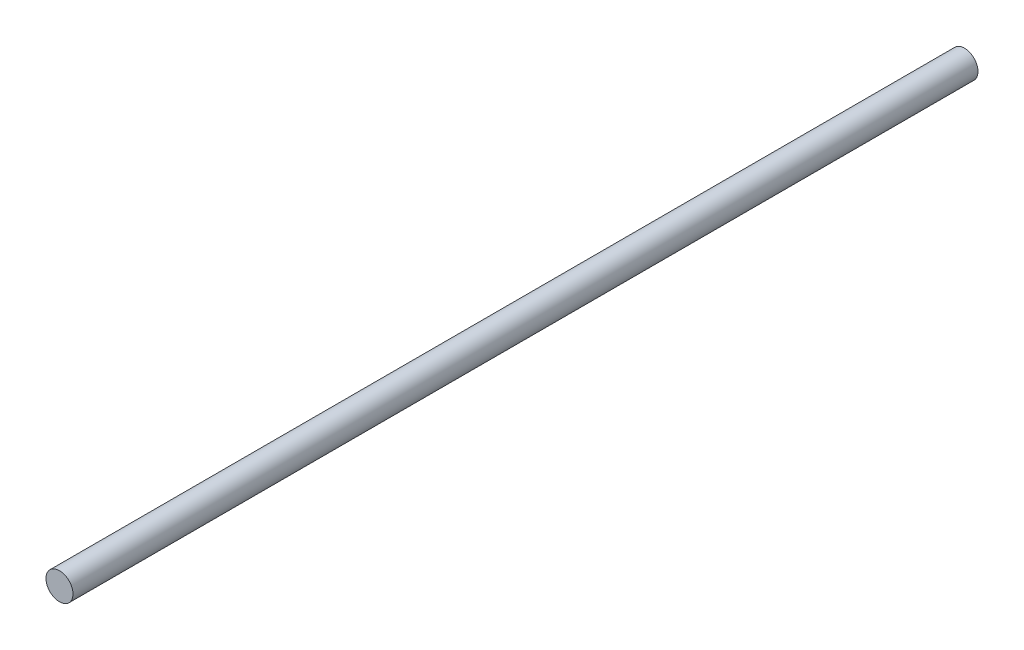
SolidWorks part; units mm, degrees
ref_plane "Front Plane" through (0, 0, 0) normal (0, 0, 1) x (1, 0, 0)
ref_plane "Top Plane" through (0, 0, 0) normal (0, 1, 0) x (1, 0, 0)
ref_plane "Right Plane" through (0, 0, 0) normal (1, 0, 0) x (0, 0, -1)
sketch "Sketch1" plane through (0, 0, 0) normal (0, 0, 1) x (1, 0, 0)
  circle A0 centre (0, 0) radius 4
  dimension "D1" = 8
extrude "Boss-Extrude1" add sketch "Sketch1" along normal blind 268
sketch "Sketch2" plane through (0, 0, 268) normal (0, 0, 1) x (1, 0, 0)
  circle A0 centre (0, 0) radius 4
curve "Helix/Spiral1" pitch 2 height 268 turns 134
sketch "Sketch3" plane through (0, 0, 0) normal (1, 0, 0) x (0, 0, -1)
  line L0 (0, 4) -> (1, 4)
  line L1 (1, 4) -> (0.75, 3.567)
  line L2 (0.75, 3.567) -> (0.25, 3.567)
  line L3 (0.25, 3.567) -> (0, 4)
  dimension "D1" = 60
  dimension "D2" = 1
  dimension "D3" = 0.5
  dimension "D4" = 0.25
equation "\"ThreadPitch\"= 2"
equation "\"D2@Sketch3\"=\"ThreadPitch\"*.5"
equation "\"D3@Sketch3\"=\"ThreadPitch\"*.25"
equation "\"D4@Sketch3\"=(\"D2@Sketch3\"-\"D3@Sketch3\")/2"
